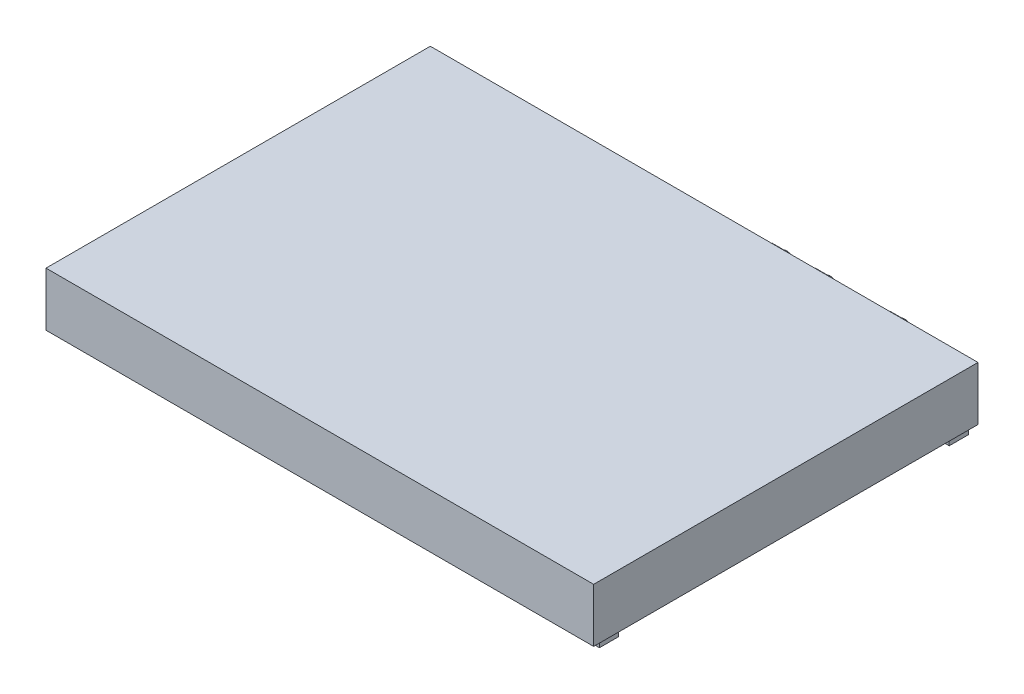
SolidWorks part; units mm, degrees
material "AISI 304"
ref_plane "Ebene vorne" through (0, 0, 0) normal (0, 0, 1) x (1, 0, 0)
ref_plane "Ebene oben" through (0, 0, 0) normal (0, 1, 0) x (1, 0, 0)
ref_plane "Ebene rechts" through (0, 0, 0) normal (1, 0, 0) x (0, 0, -1)
sketch "Skizze1" plane through (0, 0, 0) normal (1, 0, 0) x (0, 0, -1)
  line L1 (-100, -14) -> (100, -14)
  line L2 (-100, -14) -> (-100, 14)
  line L3 (-100, 14) -> (100, 14)
  line L4 (100, -14) -> (100, 14)
  line L5 (-100, -14) -> (100, 14) construction
  line L6 (-100, 14) -> (100, -14) construction
  point P0 (0, 0)
  dimension "D1" = 28
  dimension "D2" = 200
extrude "Aufsatz-Linear austragen1" add sketch "Skizze1" along normal mid plane 285
sketch "Skizze2" plane through (0, 0, -100) normal (0, 0, -1) x (-1, 0, 0)
  line L0 (-142.5, 14) -> (142.5, 14) construction
  line L1 (123, 11.75) -> (138, 11.75)
  line L2 (123, 11.75) -> (123, -8.95)
  line L3 (123, -8.95) -> (138, -8.95)
  line L4 (138, 11.75) -> (138, -8.95)
  line L5 (142.5, -14) -> (142.5, 14) construction
  dimension "D1" = 15
  dimension "D2" = 20.7
  dimension "D3" = 2.25
  dimension "D4" = 4.5
extrude "Aufsatz-Linear austragen2" add sketch "Skizze2" along normal blind 2
ref_plane "Ebene1" through (-130.5, 0, 0) normal (-1, 0, 0) x (0, 0, 1)
sketch "Skizze3" plane through (-130.5, 0, 0) normal (-1, 0, 0) x (0, 0, 1)
  line L0 (-102, 9.25) -> (-106.5, 6.6519)
  line L1 (-106.5, 6.6519) -> (-102, -6.95)
  line L2 (-102, -6.95) -> (-102, 9.25)
  line L3 (-102, 11.75) -> (-102, -8.95) construction
  line L5 (-102, 11.75) -> (-100, 11.75) construction
  point P4 (0, 0)
  point P8 (-100.952, 7.6785)
  dimension "D1" = 2
  dimension "D2" = 2.5
  dimension "D3" = 4.5
  dimension "D4" = 60
extrude "Aufsatz-Linear austragen3" add sketch "Skizze3" along normal mid plane 10
sketch "Skizze4" plane through (0, 0, -100) normal (0, 0, -1) x (-1, 0, 0)
  line L0 (-142.5, 2) -> (-96.5, 2) construction
  line L1 (-142.5, -14) -> (-142.5, 14) construction
  line L2 (-96.5, 2) -> (-57.5, 2) construction
  line L3 (-57.5, 2) -> (-35, 2) construction
  line L4 (-142.5, 14) -> (142.5, 14) construction
  point P0 (-96.5, 2)
  point P1 (-57.5, 2)
  point P2 (-35, 2)
  point P9 (-51.1912, 5.6376)
  point P10 (-35, 5.6376)
  point P11 (-57.5, 5.6376)
  point P12 (-96.5, 5.6376)
  dimension "D1" = 46
  dimension "D2" = 85
  dimension "D3" = 22.5
  dimension "D4" = 12
sketch "Skizze5" plane through (0, 0, -100) normal (0, 0, -1) x (-1, 0, 0)
  line L1 (-100.8301, -5.5) -> (-92.1699, -5.5)
  line L2 (-92.1699, -5.5) -> (-87.8397, 2)
  line L3 (-87.8397, 2) -> (-92.1699, 9.5)
  line L4 (-92.1699, 9.5) -> (-100.8301, 9.5)
  line L5 (-100.8301, 9.5) -> (-105.1603, 2)
  line L6 (-105.1603, 2) -> (-100.8301, -5.5)
  circle A0 centre (-96.5, 2) radius 7.5 construction
  dimension "D1" = 15
extrude "Aufsatz-Linear austragen4" add sketch "Skizze5" along normal blind 4.7
sketch "Skizze6" plane through (0, 0, -104.7) normal (0, 0, -1) x (-1, 0, 0)
  circle A0 centre (-96.5, 2) radius 4.5
  point P2 (0, 0)
  dimension "D1" = 9
extrude "Aufsatz-Linear austragen5" add sketch "Skizze6" along normal blind 3.3
sketch "Skizze7" plane through (0, 0, -108) normal (0, 0, -1) x (-1, 0, 0)
  circle A0 centre (-96.5, 2) radius 3.25
  point P2 (0, 0)
  dimension "D1" = 6.5
extrude "Schnitt-Linear austragen1" cut sketch "Skizze7" against normal blind 44
pattern_sketch "Skizzen-Muster1" of "Aufsatz-Linear austragen5", "Aufsatz-Linear austragen4", "Schnitt-Linear austragen1" driven by "Skizze4"
sketch "Skizze8" plane through (0, -14, 0) normal (0, -1, 0) x (1, 0, 0)
  line L0 (142.5, 100) -> (142.5, -100) construction
  line L1 (141.5, -96) -> (131.5, -96)
  line L2 (141.5, -96) -> (141.5, -86)
  line L3 (141.5, -86) -> (131.5, -86)
  line L4 (131.5, -96) -> (131.5, -86)
  line L5 (142.5, -100) -> (-142.5, -100) construction
  dimension "D1" = 1
  dimension "D2" = 4
  dimension "D3" = 10
extrude "Aufsatz-Linear austragen6" add sketch "Skizze8" along normal blind 3.1
mirror "Spiegeln1" about plane through (0, 0, 0) normal (1, 0, 0) of "Aufsatz-Linear austragen6"
mirror "Spiegeln2" about plane through (0, 0, 0) normal (0, 0, 1) of "Spiegeln1", "Aufsatz-Linear austragen6"
